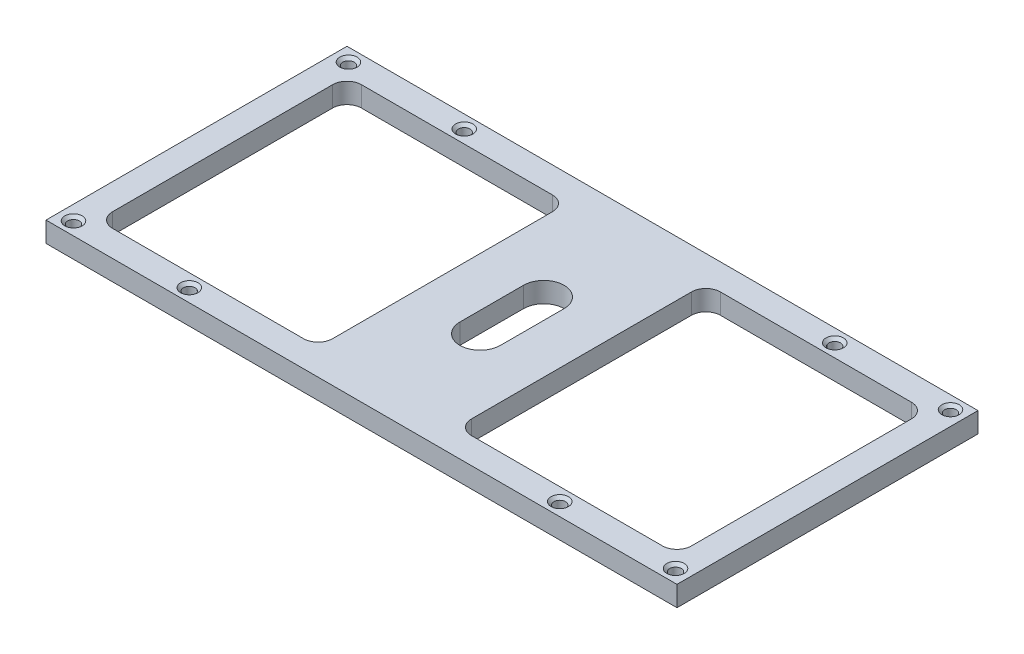
SolidWorks part; units mm, degrees
ref_plane "Front Plane" through (0, 0, 0) normal (0, 0, 1) x (1, 0, 0)
ref_plane "Top Plane" through (0, 0, 0) normal (0, 1, 0) x (1, 0, 0)
ref_plane "Right Plane" through (0, 0, 0) normal (1, 0, 0) x (0, 0, -1)
sketch "Sketch1" plane through (0, 0, 0) normal (0, 1, 0) x (1, 0, 0)
  line L0 (0, 52) -> (109, 52) construction
  line L1 (0, 0) -> (109, 0)
  line L2 (0, 0) -> (0, 52)
  line L6 (9, 52) -> (9, 9)
  line L7 (9, 9) -> (85, 9)
  line L8 (85, 52) -> (85, 9)
  line L9 (9, 52) -> (0, 52)
  line L12 (102, 52) -> (102, 41)
  line L13 (102, 41) -> (109, 41) construction
  line L18 (109, 52) -> (109, 0) construction
  line L19 (85, 52) -> (102, 52)
  line L20 (109, 0) -> (109, 34)
  arc A0 (102, 41) -> (109, 34) centre (109, 41) ccw
  dimension "D1" = 52
  dimension "D2" = 76
  dimension "D3" = 109
  dimension "D4" = 9
  dimension "D5" = 9
  dimension "D6" = 7
  dimension "D7" = 11
extrude "Boss-Extrude1" add sketch "Sketch1" along normal blind 7
fillet "Fillet1" radius 5 2 edges at (9, 3.5, -9) (85, 3.5, -9)
sketch "Sketch2" plane through (0, 7, 0) normal (0, 1, 0) x (1, 0, 0)
  line L0 (5, 4.5) -> (45, 4.5) construction
  line L1 (45, 4.5) -> (109, 4.5) construction
  line L2 (109, 0) -> (109, 34) construction
  line L3 (9, 52) -> (0, 52) construction
  circle A0 centre (5, 4.5) radius 2
  circle A1 centre (45, 4.5) radius 2
  dimension "D3" = 4
  dimension "D1" = 64
  dimension "D2" = 40
  dimension "D4" = 47.5
extrude "Cut-Extrude1" cut sketch "Sketch2" against normal through all contours A0 | A1
sketch "Sketch3" plane through (0, 0, 0) normal (0, -1, 0) x (-1, 0, 0)
  line L0 (-109, 0) -> (-109, 34) construction
  line L1 (-102, 52) -> (-85, 52) construction
  circle A0 centre (-109, 4.5) radius 3.75
  dimension "D1" = 7.5
  dimension "D2" = 47.5
extrude "Cut-Extrude2" cut sketch "Sketch3" against normal blind 3
chamfer "Chamfer1" distance 1 angle 45 2 edges at (5, 7, -2.5) (45, 7, -2.5)
mirror "Mirror1" about plane through (9, 7, -52) normal (0, 0, 1) of bodies 103
mirror "Mirror2" about plane through (109, 7, -104) normal (-1, 0, 0) of bodies 104
